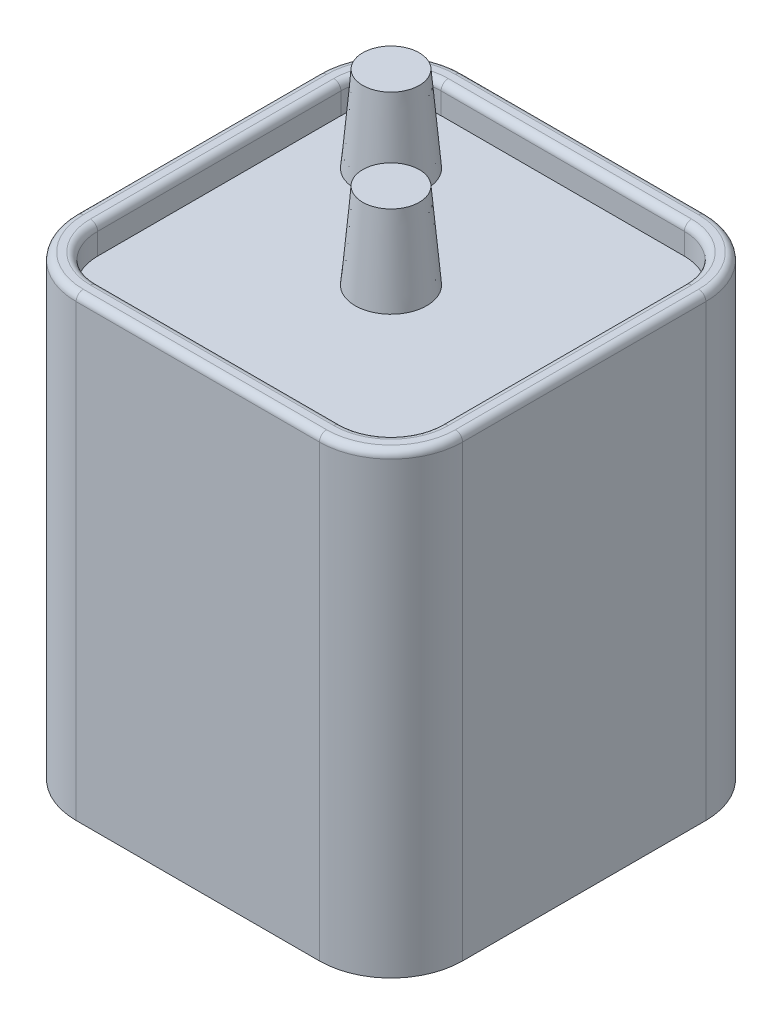
SolidWorks part; units mm, degrees
ref_plane "Front Plane" through (0, 0, 0) normal (0, 0, 1) x (1, 0, 0)
ref_plane "Top Plane" through (0, 0, 0) normal (0, 1, 0) x (1, 0, 0)
ref_plane "Right Plane" through (0, 0, 0) normal (1, 0, 0) x (0, 0, -1)
sketch "Sketch1" plane through (0, 0, 0) normal (0, 1, 0) x (1, 0, 0)
  line L1 (-34.29, -34.29) -> (34.29, -34.29)
  line L2 (-34.29, -34.29) -> (-34.29, 34.29)
  line L3 (-34.29, 34.29) -> (34.29, 34.29)
  line L4 (34.29, -34.29) -> (34.29, 34.29)
  line L5 (-34.29, -34.29) -> (34.29, 34.29) construction
  line L6 (-34.29, 34.29) -> (34.29, -34.29) construction
  point P0 (0, 0)
  dimension "D1" = 68.58
  dimension "D2" = 68.58
extrude "Base Extrude" add sketch "Sketch1" along normal blind 81.026
fillet "Side Fillets" radius 12.7 4 edges at (-34.29, 40.513, -34.29) (34.29, 40.513, -34.29) (34.29, 40.513, 34.29) (-34.29, 40.513, 34.29)
sketch "Sketch3" plane through (0, 81.026, 0) normal (0, 1, 0) x (1, 0, 0)
  line L9 (21.59, 30.48) -> (-21.59, 30.48)
  line L10 (-30.48, 21.59) -> (-30.48, -21.59)
  line L11 (-21.59, -30.48) -> (21.59, -30.48)
  line L12 (30.48, -21.59) -> (30.48, 21.59)
  line L13 (21.59, 30.48) -> (-21.59, 30.48)
  line L14 (-30.48, 21.59) -> (-30.48, -21.59)
  line L15 (-21.59, -30.48) -> (21.59, -30.48)
  line L16 (30.48, -21.59) -> (30.48, 21.59)
  arc A8 (-21.59, 30.48) -> (-30.48, 21.59) centre (-21.59, 21.59) ccw
  arc A9 (-30.48, -21.59) -> (-21.59, -30.48) centre (-21.59, -21.59) ccw
  arc A10 (21.59, -30.48) -> (30.48, -21.59) centre (21.59, -21.59) ccw
  arc A11 (30.48, 21.59) -> (21.59, 30.48) centre (21.59, 21.59) ccw
  arc A12 (-21.59, 30.48) -> (-30.48, 21.59) centre (-21.59, 21.59) ccw
  arc A13 (-30.48, -21.59) -> (-21.59, -30.48) centre (-21.59, -21.59) ccw
  arc A14 (21.59, -30.48) -> (30.48, -21.59) centre (21.59, -21.59) ccw
  arc A15 (30.48, 21.59) -> (21.59, 30.48) centre (21.59, 21.59) ccw
  dimension "D1" = 3.81
extrude "Top Cut" cut sketch "Sketch3" against normal blind 5.08
fillet "Top Face Fillet" radius 1.27 16 edges at (30.5703, 81.026, -30.5703) (34.29, 81.026, 0) (30.5703, 81.026, 30.5703) (0, 81.026, 34.29) (-30.5703, 81.026, 30.5703) (-34.29, 81.026, 0) (-30.5703, 81.026, -30.5703) (0, 81.026, -34.29) (-27.8762, 81.026, -27.8762) (-30.48, 81.026, 0) (-27.8762, 81.026, 27.8762) (0, 81.026, 30.48) (27.8762, 81.026, 27.8762) (30.48, 81.026, 0) (27.8762, 81.026, -27.8762) (0, 81.026, -30.48)
sketch "Sketch4" plane through (0, 75.946, 0) normal (0, 1, 0) x (1, 0, 0)
  line L0 (-17.9605, 17.9605) -> (0, 0) construction
  line L1 (0, -43.3102) -> (0, 40.3476) construction
  circle A0 centre (0, 0) radius 6.35
  circle A1 centre (-17.9605, 17.9605) radius 6.35
  dimension "D1" = 12.7
  dimension "D2" = 25.4
  dimension "D3" = 45
extrude "Terminals" add sketch "Sketch4" along normal blind 15.24 draft 5 contours A0 | A1
